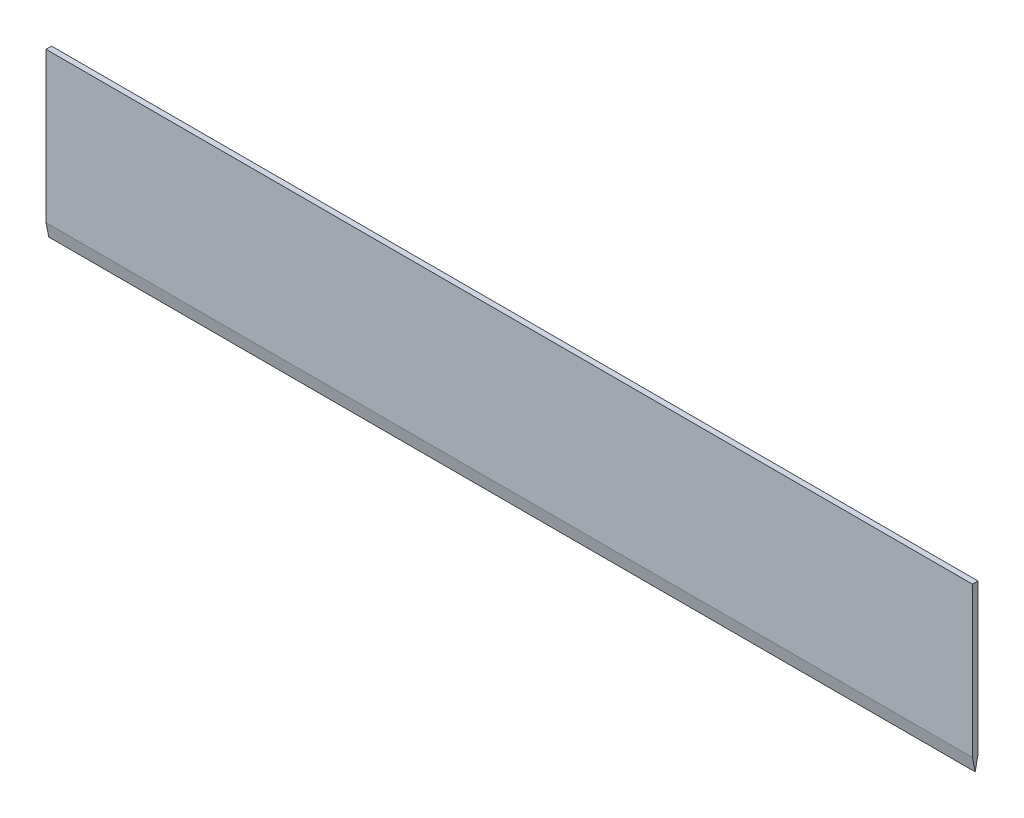
SolidWorks part; units mm, degrees
material "AISI 1020 Aço, laminado a frio"
ref_plane "Plano frontal" through (0, 0, 0) normal (0, 0, 1) x (1, 0, 0)
ref_plane "Plano superior" through (0, 0, 0) normal (0, 1, 0) x (1, 0, 0)
ref_plane "Plano direito" through (0, 0, 0) normal (1, 0, 0) x (0, 0, -1)
sketch "Esboço1" plane through (0, 0, 0) normal (0, 0, 1) x (1, 0, 0)
  line L1 (-50, 9) -> (50, 9)
  line L2 (-50, 9) -> (-50, -9)
  line L3 (-50, -9) -> (50, -9)
  line L4 (50, 9) -> (50, -9)
  dimension "D1" = 100
  dimension "D2" = 18
  dimension "D3" = 50
  dimension "D4" = 9
extrude "Ressalto-extrusão1" add sketch "Esboço1" along normal blind 0.6
sketch "Esboço2" plane through (50, 0, 0) normal (1, 0, 0) x (0, 0, -1)
  line L0 (-0.3, -9) -> (-0.6, -7.5)
  line L1 (-0.6, -9) -> (0, -9) construction
  line L2 (-0.6, -9) -> (-0.6, 9) construction
  line L3 (-0.6, -7.5) -> (-0.6, -9)
  line L4 (-0.6, -9) -> (0, -9)
  line L5 (0, -9) -> (0, -7.5)
  line L6 (0, -9) -> (0, 9) construction
  line L7 (0, -7.5) -> (-0.3, -9)
  line L9 (-0.6, 9) -> (0, 9)
  line L10 (-0.6, 9) -> (-0.6, 8.7)
  line L11 (-0.6, 8.7) -> (0, 8.7)
  line L12 (0, 9) -> (0, 8.7)
  line M4 (0, -9) -> (0, 9)
  line M5 (0, 9) -> (-0.6, 9)
  line M6 (-0.6, 9) -> (-0.6, -9)
  line M7 (-0.6, -9) -> (0, -9)
  dimension "D1" = 1.5
  dimension "D2" = 1.5
  dimension "D3" = 0.3
extrude "Corte-extrusão1" cut sketch "Esboço2" against normal blind 100 contours L0 M7 M6 | L7 M4 M7 | L11 M6 M4 M5
